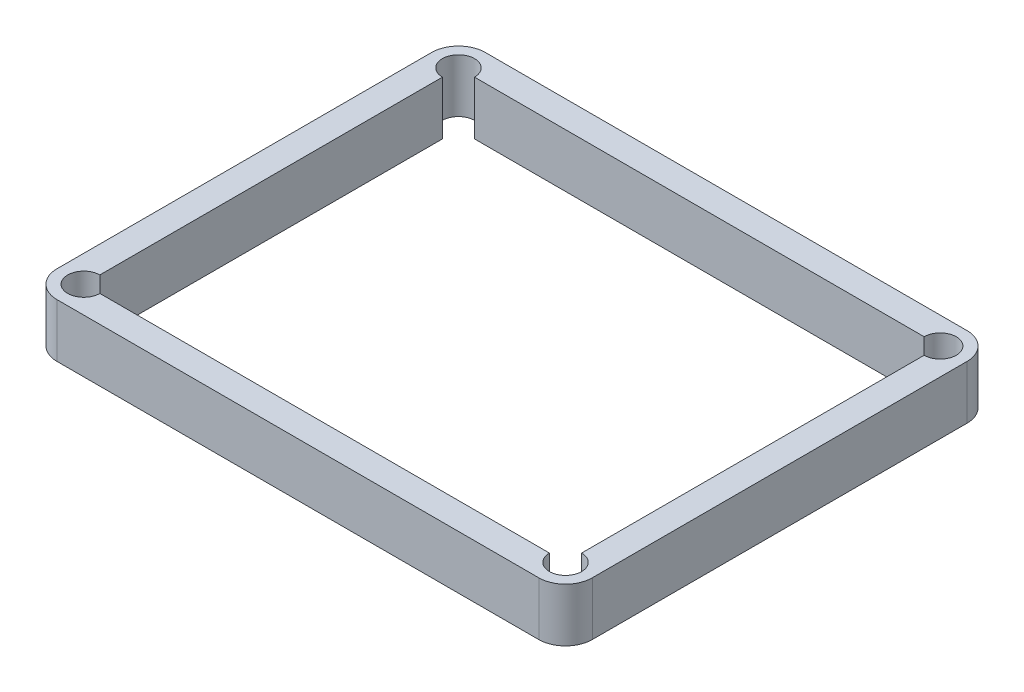
SolidWorks part; units mm, degrees
material "有机玻璃 (TM) GS 丙烯酸铸钣"
ref_plane "前视基准面" through (0, 0, 0) normal (0, 0, 1) x (1, 0, 0)
ref_plane "上视基准面" through (0, 0, 0) normal (0, 1, 0) x (1, 0, 0)
ref_plane "右视基准面" through (0, 0, 0) normal (1, 0, 0) x (0, 0, -1)
sketch "草图1" plane through (0, 0, 0) normal (0, 1, 0) x (1, 0, 0)
  line L1 (-55.214, 19.5444) -> (-10.214, 19.5444)
  line L2 (-57.714, 17.0444) -> (-57.714, -17.9556)
  line L3 (-55.214, -20.4556) -> (-10.214, -20.4556)
  line L4 (-7.714, 17.0444) -> (-7.714, -17.9556)
  arc A0 (-55.214, 19.5444) -> (-57.714, 17.0444) centre (-55.214, 17.0444) ccw
  arc A1 (-7.714, 17.0444) -> (-10.214, 19.5444) centre (-10.214, 17.0444) ccw
  arc A2 (-57.714, -17.9556) -> (-55.214, -20.4556) centre (-55.214, -17.9556) ccw
  arc A3 (-10.214, -20.4556) -> (-7.714, -17.9556) centre (-10.214, -17.9556) ccw
extrude "凸台-拉伸3" add sketch "草图1" along normal blind 5
sketch "草图7" plane through (0, 5, 0) normal (0, 1, 0) x (1, 0, 0)
  circle A4 centre (-55.214, 17.0444) radius 1.5
  circle A5 centre (-10.214, 17.0444) radius 1.5
  circle A6 centre (-55.214, -17.9556) radius 1.5
  circle A7 centre (-10.214, -17.9556) radius 1.5
extrude "切除-拉伸1" cut sketch "草图7" against normal through all
sketch "草图8" plane through (0, 5, 0) normal (0, 1, 0) x (1, 0, 0)
  line L1 (-55.214, 17.0444) -> (-10.214, 17.0444)
  line L2 (-55.214, 17.0444) -> (-55.214, -17.9556)
  line L3 (-55.214, -17.9556) -> (-10.214, -17.9556)
  line L4 (-10.214, 17.0444) -> (-10.214, -17.9556)
extrude "切除-拉伸2" cut sketch "草图8" against normal through all
